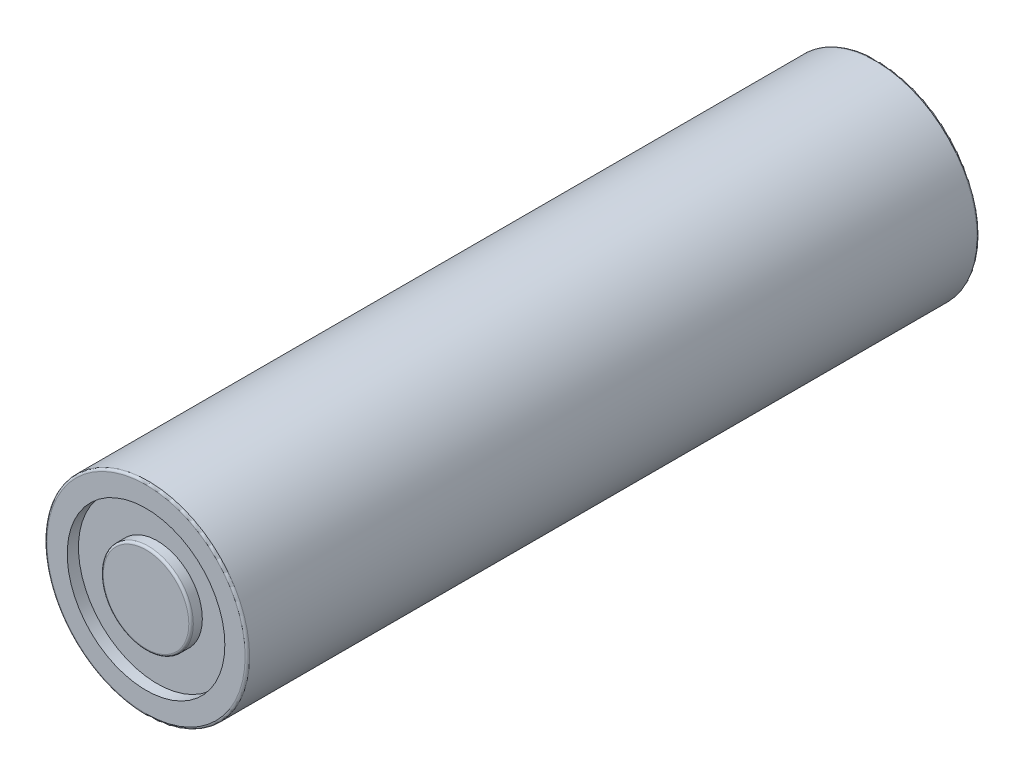
SolidWorks part; units mm, degrees
ref_plane "Top Plane" through (0, 0, 0) normal (0, 0, 1) x (1, 0, 0)
ref_plane "Right Plane" through (0, 0, 0) normal (0, 1, 0) x (1, 0, 0)
ref_plane "Front Plane" through (0, 0, 0) normal (1, 0, 0) x (0, 0, -1)
sketch "Sketch1" plane through (0, 0, 0) normal (0, 0, 1) x (1, 0, 0)
  circle A0 centre (0, 0) radius 9
  dimension "D1" = 18
extrude "Boss-Extrude1" add sketch "Sketch1" along normal mid plane 65
sketch "Sketch2" plane through (0, 0, 32.5) normal (0, 0, 1) x (1, 0, 0)
  circle A0 centre (0, 0) radius 7
  circle A1 centre (0, 0) radius 4
  dimension "D1" = 14
  dimension "D2" = 8
extrude "Cut-Extrude1" cut sketch "Sketch2" against normal blind 1
fillet "Fillet1" radius 0.2 3 edges at (9, 0, -32.5) (9, 0, 32.5) (4, 0, 32.5)
